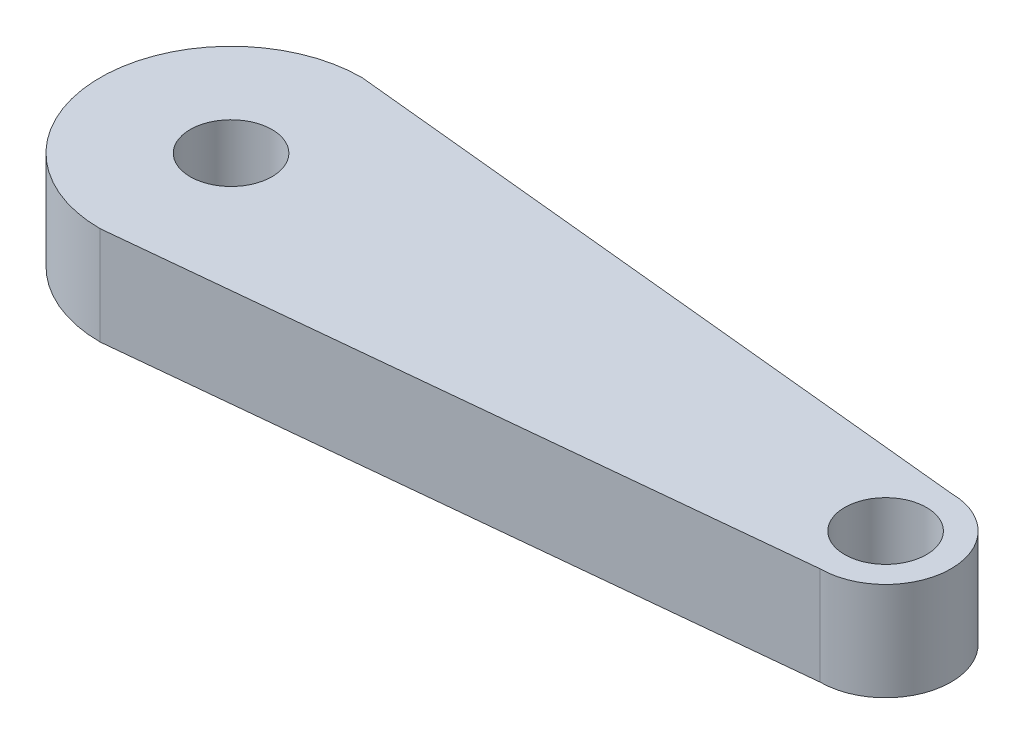
SolidWorks part; units mm, degrees
ref_plane "Front Plane" through (0, 0, 0) normal (0, 0, 1) x (1, 0, 0)
ref_plane "Top Plane" through (0, 0, 0) normal (0, 1, 0) x (1, 0, 0)
ref_plane "Right Plane" through (0, 0, 0) normal (1, 0, 0) x (0, 0, -1)
sketch "Sketch2" plane through (0, 0, 0) normal (0, 1, 0) x (1, 0, 0)
  line L0 (0, 80) -> (400, 40)
  line L1 (0, -80) -> (400, -40)
  arc A0 (0, 80) -> (0, -80) centre (0, 0) ccw
  arc A1 (400, -40) -> (400, 40) centre (400, 0) ccw
  dimension "D1" = 160
  dimension "D2" = 80
  dimension "D3" = 400
extrude "Boss-Extrude1" add sketch "Sketch2" along normal blind 60
sketch "Sketch3" plane through (0, 60, 0) normal (0, 1, 0) x (1, 0, 0)
  circle A0 centre (0, 0) radius 25
  circle A1 centre (400, 0) radius 25
  dimension "D1" = 50
  dimension "D2" = 50
extrude "Cut-Extrude1" cut sketch "Sketch3" against normal blind 50
